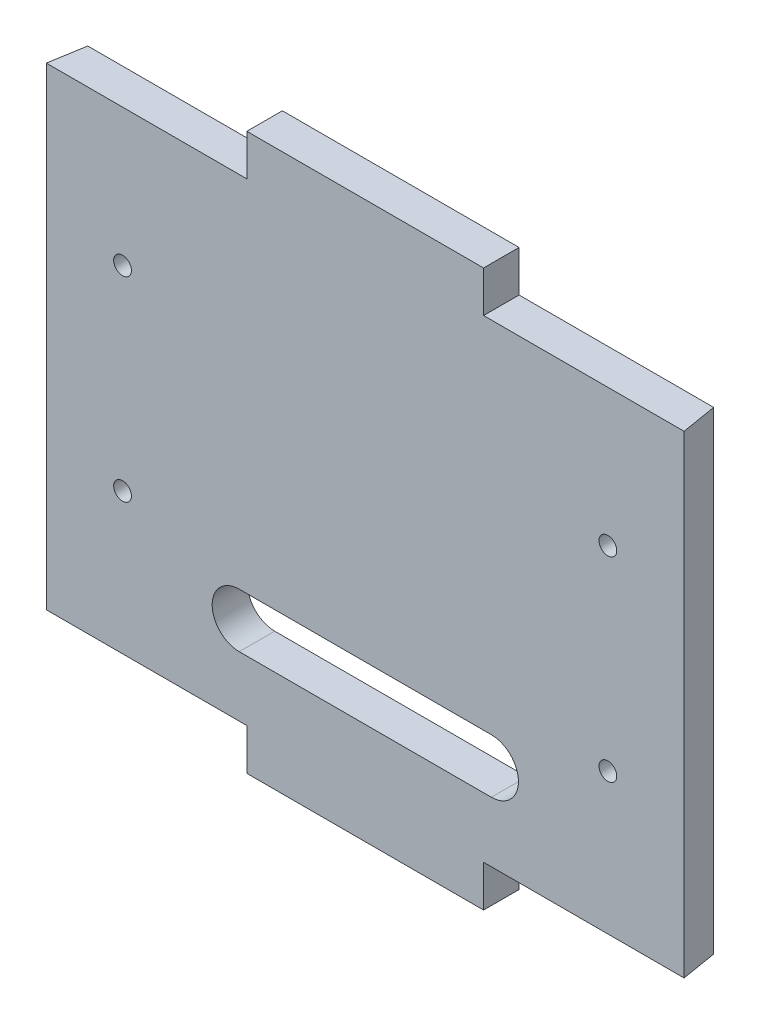
SolidWorks part; units mm, degrees
ref_plane "Front Plane" through (0, 0, 0) normal (0, 0, 1) x (1, 0, 0)
ref_plane "Top Plane" through (0, 0, 0) normal (0, 1, 0) x (1, 0, 0)
ref_plane "Right Plane" through (0, 0, 0) normal (1, 0, 0) x (0, 0, -1)
sketch "Model" plane through (0, 0, 0) normal (0, 0, 1) x (1, 0, 0)
  line L0 (70.2168, 10.8027) -> (53.2769, 10.8027)
  line L1 (33.2769, 10.8027) -> (16.337, 10.8027)
  line L2 (33.2769, 10.8027) -> (33.2769, 9.3027)
  line L3 (53.2769, 9.3027) -> (53.2769, 10.8027)
  line L4 (16.337, 10.8027) -> (16.337, 50.8027)
  line L5 (70.2168, 50.8027) -> (70.2168, 10.8027)
  line L6 (70.2168, 50.8027) -> (53.2769, 50.8027)
  line L7 (33.2769, 50.8027) -> (16.337, 50.8027)
  line L8 (33.2769, 50.8027) -> (33.2769, 52.2831)
  line L9 (33.2769, 52.2831) -> (53.2769, 52.2831)
  line L10 (53.2769, 52.2831) -> (53.2769, 50.8027)
  line L11 (33.2769, 9.3027) -> (53.2769, 9.3027)
extrude "Boss-Extrude1" add sketch "Model" along normal blind 3 contours L4 L7 L8 L9 L10 L6 L5 L0 L3 L11 L2 L1
sketch "Sketch1" plane through (0, 9.3027, 0) normal (0, -1, 0) x (1, 0, 0)
  line L4 (33.2769, 0) -> (53.2769, 0)
  line L5 (53.2769, 0) -> (53.2769, 3)
  line L6 (53.2769, 3) -> (33.2769, 3)
  line L7 (33.2769, 3) -> (33.2769, 0)
  line L8 (33.2769, 0) -> (53.2769, 0)
  line L9 (53.2769, 0) -> (53.2769, 3)
  line L10 (53.2769, 3) -> (33.2769, 3)
  line L11 (33.2769, 3) -> (33.2769, 0)
  dimension "D1" = 0
extrude "Boss-Extrude2" add sketch "Sketch1" along normal blind 2
sketch "Sketch2" plane through (0, 52.2831, 0) normal (0, 1, 0) x (1, 0, 0)
  line L4 (53.2769, 0) -> (33.2769, 0)
  line L5 (33.2769, 0) -> (33.2769, -3)
  line L6 (33.2769, -3) -> (53.2769, -3)
  line L7 (53.2769, -3) -> (53.2769, 0)
  line L8 (53.2769, 0) -> (33.2769, 0)
  line L9 (33.2769, 0) -> (33.2769, -3)
  line L10 (33.2769, -3) -> (53.2769, -3)
  line L11 (53.2769, -3) -> (53.2769, 0)
  dimension "D1" = 0
extrude "Boss-Extrude3" add sketch "Sketch2" along normal blind 2
sketch "Sketch3" plane through (0, 50.8027, 0) normal (0, 1, 0) x (1, 0, 0)
  line L4 (43.2769, -3) -> (43.2769, 8.2261) construction
  line L5 (33.2769, -3) -> (53.2769, -3) construction
  line L9 (70.2168, 0) -> (69.7168, 0)
  line L10 (70.2168, 0) -> (53.2769, 0) construction
  line L11 (69.7168, 0) -> (70.2168, -3)
  line L12 (70.2168, -3) -> (70.2168, 0)
  line L13 (16.337, -3) -> (16.337, 0)
  line L14 (16.837, 0) -> (16.337, -3)
  line L15 (16.337, 0) -> (16.837, 0)
extrude "Cut-Extrude4" cut sketch "Sketch3" against normal blind 44
sketch "Sketch4" plane through (0, 0, 3) normal (0, 0, 1) x (1, 0, 0)
  line L0 (43.2769, 54.2831) -> (43.2769, 7.3027) construction
  line L1 (33.2769, 54.2831) -> (53.2769, 54.2831) construction
  line L2 (53.2769, 7.3027) -> (33.2769, 7.3027) construction
  line L3 (43.2769, 39.2186) -> (22.7769, 39.2186) construction
  line L4 (22.7769, 39.2186) -> (22.7769, 22.7186) construction
  circle A0 centre (22.7769, 39.2186) radius 0.75
  circle A1 centre (22.7769, 22.7186) radius 0.75
  circle A2 centre (63.7769, 22.7186) radius 0.75
  circle A3 centre (63.7769, 39.2186) radius 0.75
  dimension "D1" = 1.5
  dimension "D2" = 1.5
extrude "Cut-Extrude5" cut sketch "Sketch4" against normal blind 16
sketch "Sketch5" plane through (0, 0, 3) normal (0, 0, 1) x (1, 0, 0)
  line L0 (22.7769, 22.7186) -> (63.7769, 22.7186) construction
  line L1 (43.2769, 22.7186) -> (43.2769, 18.1729) construction
  line L2 (32.6334, 18.1729) -> (53.9358, 18.1729) construction
  line L3 (32.6334, 20.4599) -> (53.9358, 20.4599)
  line L4 (32.6334, 15.886) -> (53.9358, 15.886)
  arc A0 (32.6334, 20.4599) -> (32.6334, 15.886) centre (32.6334, 18.1729) ccw
  arc A1 (53.9358, 15.886) -> (53.9358, 20.4599) centre (53.9358, 18.1729) ccw
  point P8 (43.2846, 18.1729)
extrude "Cut-Extrude6" cut sketch "Sketch5" against normal blind 16
